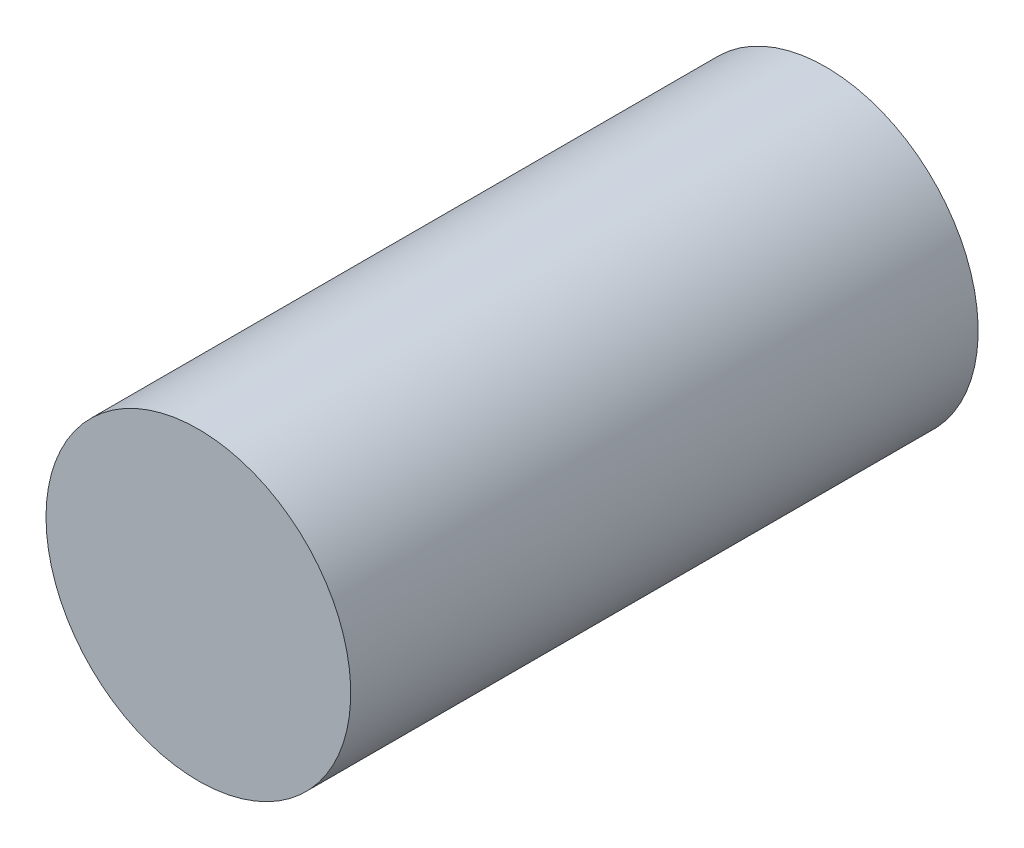
SolidWorks part; units mm, degrees
ref_plane "Front Plane" through (0, 0, 0) normal (0, 0, 1) x (1, 0, 0)
ref_plane "Top Plane" through (0, 0, 0) normal (0, 1, 0) x (1, 0, 0)
ref_plane "Right Plane" through (0, 0, 0) normal (1, 0, 0) x (0, 0, -1)
sketch "Sketch1" plane through (0, 0, 0) normal (0, 0, 1) x (1, 0, 0)
  circle A0 centre (0, 0) radius 1.7
  dimension "D1" = 3.4
extrude "Boss-Extrude1" add sketch "Sketch1" along normal blind 7 contours A0
